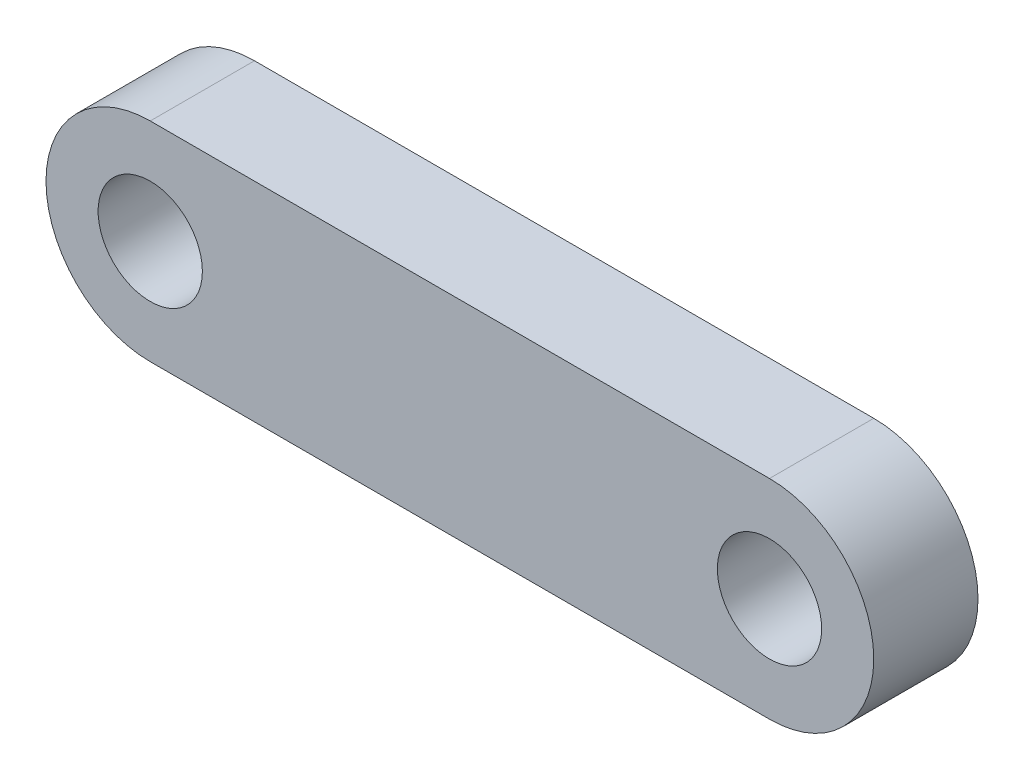
SolidWorks part; units mm, degrees
ref_plane "前基準面" through (0, 0, 0) normal (0, 0, 1) x (1, 0, 0)
ref_plane "上基準面" through (0, 0, 0) normal (0, 1, 0) x (1, 0, 0)
ref_plane "右基準面" through (0, 0, 0) normal (1, 0, 0) x (0, 0, -1)
sketch "草圖1" plane through (0, 0, 0) normal (0, 0, 1) x (1, 0, 0)
  line L0 (-5.94, 2.0003) -> (5.94, 2.0003)
  line L1 (-5.94, -1.9997) -> (5.94, -1.9997)
  arc A0 (-5.94, 2.0003) -> (-5.94, -1.9997) centre (-5.94, 0.0003) ccw
  arc A1 (5.94, -1.9997) -> (5.94, 2.0003) centre (5.94, 0.0003) ccw
  circle A2 centre (-5.94, 0.0003) radius 1
  circle A3 centre (5.94, 0.0003) radius 1
  dimension "D1" = 11.88
  dimension "D2" = 2
  dimension "D3" = 2
  dimension "D4" = 2
  dimension "D5" = 5.94
extrude "填料-伸長1" add sketch "草圖1" along normal blind 2
